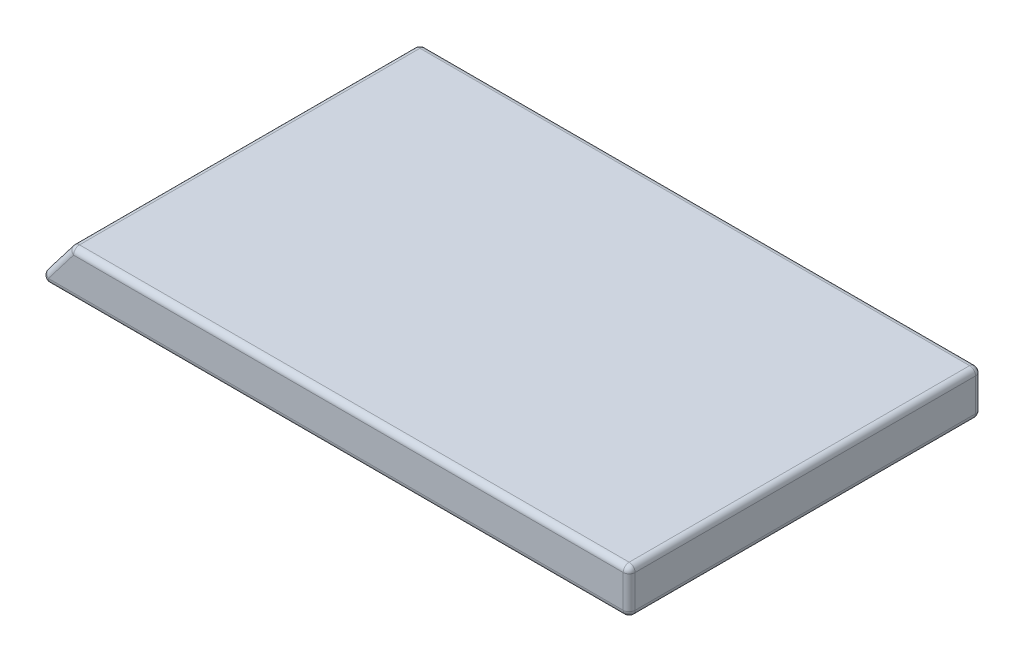
SolidWorks part; units mm, degrees
ref_plane "Front Plane" through (0, 0, 0) normal (0, 0, 1) x (1, 0, 0)
ref_plane "Top Plane" through (0, 0, 0) normal (0, 1, 0) x (1, 0, 0)
ref_plane "Right Plane" through (0, 0, 0) normal (1, 0, 0) x (0, 0, -1)
sketch "Sketch1" plane through (0, 0, 0) normal (0, 0, 1) x (1, 0, 0)
  line L0 (0, 0) -> (-996, 0)
  line L1 (-996, 0) -> (-938.4505, 75)
  line L2 (-938.4505, 75) -> (0, 75)
  line L3 (0, 75) -> (0, 0)
  dimension "D1" = 75
  dimension "D2" = 996
  dimension "D3" = 52.5
extrude "Boss-Extrude1" add sketch "Sketch1" along normal mid plane 592
fillet "Fillet1" radius 10 12 edges at (-967.2252, 37.5, -296) (-996, 0, 0) (-498, 0, -296) (0, 0, 0) (0, 37.5, -296) (-498, 0, 296) (-967.2252, 37.5, 296) (0, 37.5, 296) (0, 75, 0) (-469.2252, 75, 296) (-938.4505, 75, 0) (-469.2252, 75, -296)
